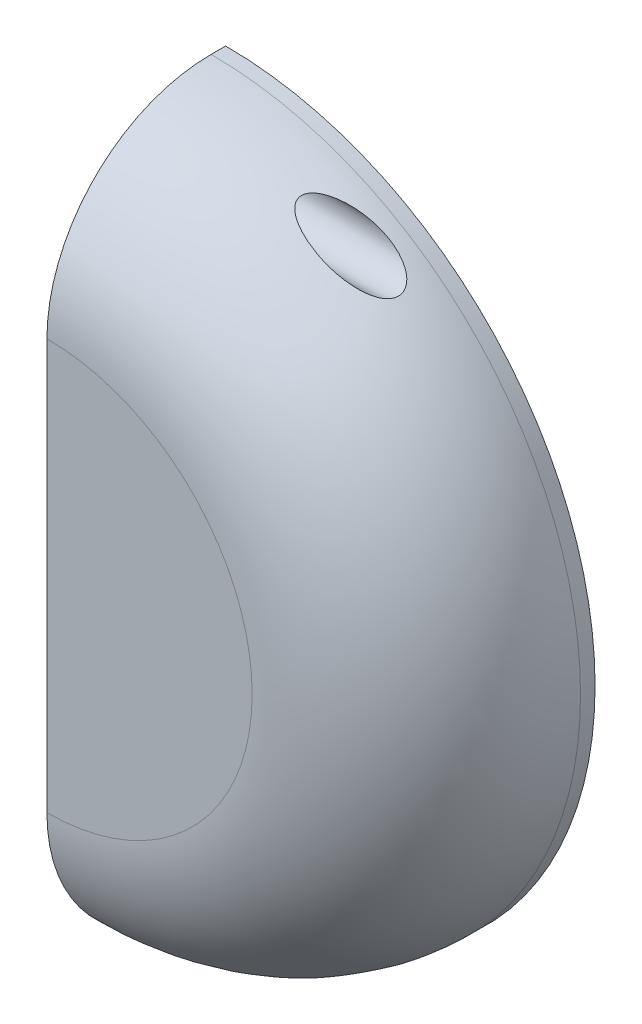
SolidWorks part; units mm, degrees
ref_plane "前视基准面" through (0, 0, 0) normal (0, 0, 1) x (1, 0, 0)
ref_plane "上视基准面" through (0, 0, 0) normal (0, 1, 0) x (1, 0, 0)
ref_plane "右视基准面" through (0, 0, 0) normal (1, 0, 0) x (0, 0, -1)
sketch "草图1" plane through (0, 0, 0) normal (0, 0, 1) x (1, 0, 0)
  circle A0 centre (0, 0) radius 49.5
  dimension "D1" = 99
extrude "凸台-拉伸1" add sketch "草图1" along normal blind 23.95
sketch "草图2" plane through (0, 0, 0) normal (0, 0, 1) x (1, 0, 0)
  line L0 (0, 51.4838) -> (0, -54.1458)
  line L1 (0, -54.1458) -> (-51.8564, -54.1458)
  line L2 (-51.8564, -54.1458) -> (-51.8564, 51.4838)
  line L3 (-51.8564, 51.4838) -> (0, 51.4838)
extrude "切除-拉伸1" cut sketch "草图2" along normal up to next
fillet "圆角1" radius 22 1 edges at (49.5, 0, 23.95)
shell "抽壳1" thickness 2
sketch "草图3" plane through (2, 0, 0) normal (1, 0, 0) x (0, 0, -1)
  line L4 (-1.95, -47.4579) -> (0, -47.4579)
  line L5 (0, -47.4579) -> (0, 47.4579)
  line L7 (-21.95, 27.4272) -> (-21.95, -27.4272)
  line L9 (0, -47.4579) -> (0, 47.4579)
  line L11 (-21.95, 27.4272) -> (-21.95, -27.4272)
  line L12 (-1.95, -47.4579) -> (0, -47.4579)
  line L14 (0, 47.4579) -> (-1.95, 47.4579)
  line L15 (0, 47.4579) -> (-1.95, 47.4579)
  spline S2 degree 3 poles (1916.1064, 453.226) (531.8804, 209.3456) (-38.9902, 56.1885) (-21.4349, -31.9952) (-21.2738, -32.6365) (-20.8934, -33.8889) (-20.4536, -35.1168) (-19.8965, -36.2965) (-19.28, -37.4517) (-18.9398, -38.02) (-17.8438, -39.6609) (-17.0163, -40.6686) (-15.6331, -42.0538) (-15.1482, -42.4943) (-14.1292, -43.3316) (-13.5995, -43.7244) (-11.9691, -44.8142) (-10.8203, -45.4292) (-9.0037, -46.183) (-8.3792, -46.4068) (-7.1225, -46.788) (-6.4886, -46.9465) (63.7341, -60.9186) (196.1564, 294.1759) (537.4608, 1875.6596) knots -8.33849 -8.33849 -8.33849 -8.33849 0.125 0.125 0.1875 0.1875 0.25 0.3125 0.3125 0.375 0.375 0.5 0.5 0.5625 0.5625 0.625 0.625 0.75 0.75 0.8125 0.8125 0.875 0.875 7.679216 7.679216 7.679216 7.679216 only from (-21.95, -27.4272) to (-1.95, -47.4579)
  spline S3 degree 3 poles (-21.95, -27.4272) (-21.95, -28.7488) (-21.8209, -30.0559) (-21.4349, -31.9952) (-21.2738, -32.6365) (-20.8934, -33.8889) (-20.4536, -35.1168) (-19.8965, -36.2965) (-19.28, -37.4517) (-18.9398, -38.02) (-17.8438, -39.6609) (-17.0163, -40.6686) (-15.6331, -42.0538) (-15.1482, -42.4943) (-14.1292, -43.3316) (-13.5995, -43.7244) (-11.9691, -44.8142) (-10.8203, -45.4292) (-9.0037, -46.183) (-8.3792, -46.4068) (-7.1225, -46.788) (-6.4886, -46.9465) (-4.5712, -47.328) (-3.2716, -47.4579) (-1.95, -47.4579) knots 0 0 0 0 0.125 0.125 0.1875 0.1875 0.25 0.3125 0.3125 0.375 0.375 0.5 0.5 0.5625 0.5625 0.625 0.625 0.75 0.75 0.8125 0.8125 0.875 0.875 1 1 1 1
  spline S4 degree 3 poles (470.8626, -1892.4798) (238.2253, -538.2911) (83.8123, 65.0352) (-6.5225, 46.9389) (-7.1609, 46.7776) (-8.4112, 46.3958) (-9.6379, 45.9543) (-10.8178, 45.3945) (-11.9739, 44.7745) (-12.5425, 44.4323) (-14.1778, 43.3348) (-15.1835, 42.5056) (-16.5671, 41.1177) (-17.0076, 40.6305) (-17.844, 39.6075) (-18.2334, 39.0797) (-19.3185, 37.4486) (-19.9317, 36.2983) (-20.6834, 34.4769) (-20.906, 33.8518) (-21.2845, 32.5969) (-21.4419, 31.9638) (-35.2569, -37.8697) (313.8093, -171.0914) (1898.2121, -522.3522) knots -8.533115 -8.533115 -8.533115 -8.533115 0.125 0.125 0.1875 0.1875 0.25 0.3125 0.3125 0.375 0.375 0.5 0.5 0.5625 0.5625 0.625 0.625 0.75 0.75 0.8125 0.8125 0.875 0.875 7.647169 7.647169 7.647169 7.647169 only from (-1.95, 47.4579) to (-21.95, 27.4272)
  spline S5 degree 3 poles (-1.95, 47.4579) (-3.2719, 47.4579) (-4.5802, 47.328) (-6.5225, 46.9389) (-7.1609, 46.7776) (-8.4112, 46.3958) (-9.6379, 45.9543) (-10.8178, 45.3945) (-11.9739, 44.7745) (-12.5425, 44.4323) (-14.1778, 43.3348) (-15.1835, 42.5056) (-16.5671, 41.1177) (-17.0076, 40.6305) (-17.844, 39.6075) (-18.2334, 39.0797) (-19.3185, 37.4486) (-19.9317, 36.2983) (-20.6834, 34.4769) (-20.906, 33.8518) (-21.2845, 32.5969) (-21.4419, 31.9638) (-21.8209, 30.048) (-21.95, 28.749) (-21.95, 27.4272) knots 0 0 0 0 0.125 0.125 0.1875 0.1875 0.25 0.3125 0.3125 0.375 0.375 0.5 0.5 0.5625 0.5625 0.625 0.625 0.75 0.75 0.8125 0.8125 0.875 0.875 1 1 1 1
  dimension "D1" = 0
extrude "切除-拉伸2" cut sketch "草图3" against normal up to next
sketch "草图4" plane through (0, 0, 0) normal (0, 0, -1) x (-1, 0, 0)
  line L0 (0, 36.5) -> (-30.3974, 36.5)
  line L1 (0, 47.5) -> (0, 36.5)
  arc A1 (-2, 47.4579) -> (-2, -47.4579) centre (0, 0) ccw construction
  arc A2 (0, 47.5) -> (-30.3974, 36.5) centre (0, 0) ccw
extrude "凸台-拉伸2" add sketch "草图4" against normal up to next
mirror "镜向1" about plane through (0, 0, 0) normal (0, 1, 0) of "凸台-拉伸2"
hole_wizard "M3 螺纹孔的螺纹孔钻头1" positions "草图7" profile "草图8" hole size "M3" standard "GB" end condition up to next
sketch "草图7" plane through (0, 0, 0) normal (-1, 0, 0) x (0, 0, 1)
  line L0 (0, 36.5) -> (0, 49.5) construction
  line L1 (0, -49.5) -> (0, -36.5) construction
  line L3 (13.3993, 0) -> (-13.3993, 0) construction
  point P0 (7.25, 42)
  point P2 (7.25, -42)
  dimension "D1" = 7.25
  dimension "D2" = 7.25
  dimension "D3" = 42
  dimension "D4" = 42
sketch "草图8" plane through (0, 42, 7.25) normal (0, 1, 0) x (0, 0, 1)
  line L0 (0, 0) -> (0, 24.9504)
  line L1 (0, 24.9504) -> (1.25, 24.9504)
  line L2 (1.25, 24.9504) -> (1.25, 0.025)
  line L3 (1.25, 0.025) -> (1.275, 0)
  line L5 (1.275, 0) -> (0, 0)
  line L6 (-1.25, 0.025) -> (-1.275, 0) construction
  line L11 (0, -6.35) -> (0, 107.95) construction
  dimension "通孔孔直径" = 2.5
  dimension "通孔孔深度" = 24.9504
  dimension "近端锥形沉头孔直径" = 2.55
  dimension "近端锥形沉头孔角度" = 90
sketch "草图9" plane through (0, 0, 0) normal (-1, 0, 0) x (0, 0, 1)
  circle A0 centre (7.25, 42) radius 3.25
  circle A1 centre (7.25, -42) radius 3.25
  dimension "D1" = 6.5
  dimension "D2" = 6.5
extrude "切除-拉伸3" cut sketch "草图9" against normal up to next from offset 10 offset against normal yes
